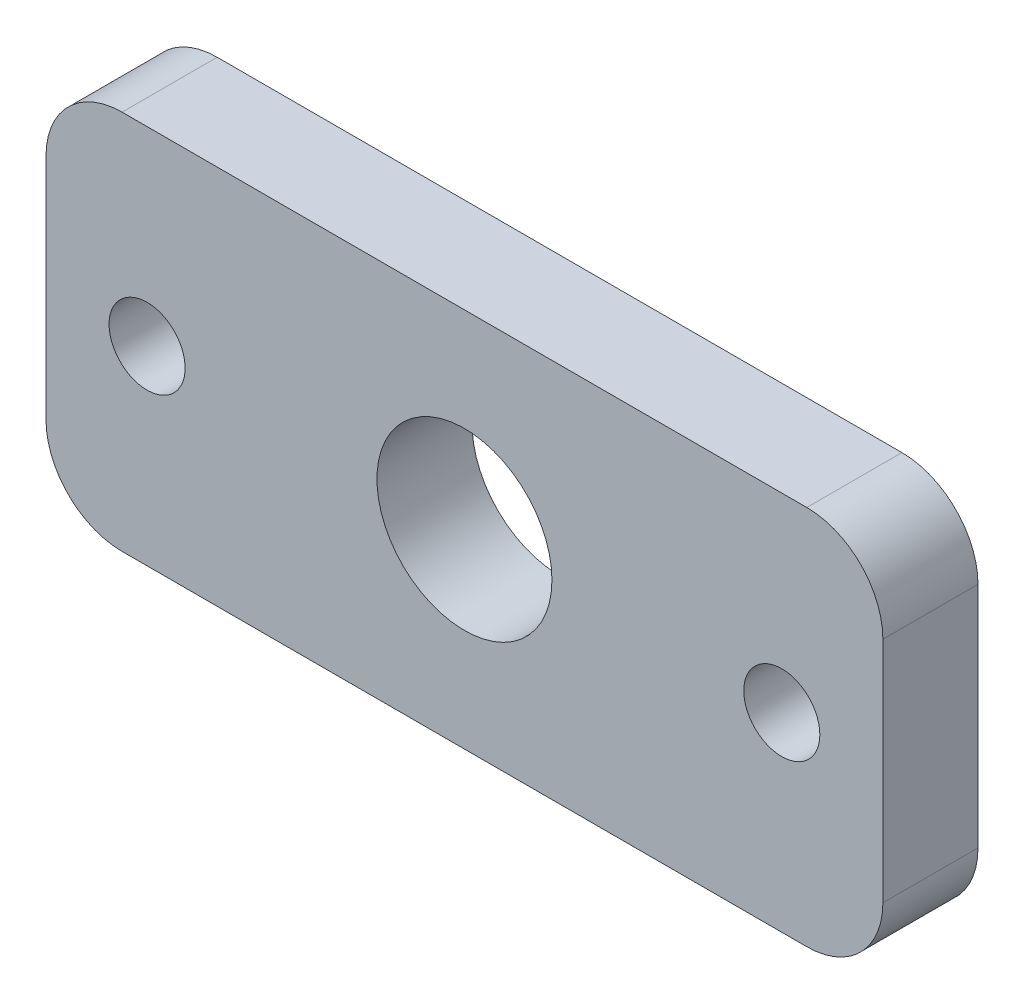
SolidWorks part; units mm, degrees
ref_plane "Front Plane" through (0, 0, 0) normal (0, 0, 1) x (1, 0, 0)
ref_plane "Top Plane" through (0, 0, 0) normal (0, 1, 0) x (1, 0, 0)
ref_plane "Right Plane" through (0, 0, 0) normal (1, 0, 0) x (0, 0, -1)
sketch "Sketch1" plane through (0, 0, 0) normal (0, 0, 1) x (1, 0, 0)
  line L1 (-27.94, 12.7) -> (27.94, 12.7)
  line L2 (-27.94, 12.7) -> (-27.94, -12.7)
  line L3 (-27.94, -12.7) -> (27.94, -12.7)
  line L4 (27.94, 12.7) -> (27.94, -12.7)
  line L5 (-27.94, 12.7) -> (27.94, -12.7) construction
  line L6 (-27.94, -12.7) -> (27.94, 12.7) construction
  circle A0 centre (0, 0) radius 5.842
  point P0 (0, 0)
  dimension "D3" = 11.684
  dimension "D1" = 25.4
  dimension "D2" = 55.88
extrude "Boss-Extrude1" add sketch "Sketch1" along normal mid plane 6.35
sketch "Sketch2" plane through (0, 0, 3.175) normal (0, 0, 1) x (1, 0, 0)
  line L1 (0, 0) -> (0, 6.9804) construction
  circle A0 centre (21.19, 0) radius 2.54
  circle A1 centre (-21.19, 0) radius 2.54
  dimension "D1" = 5.08
  dimension "D2" = 42.38
extrude "4-40" cut sketch "Sketch2" against normal through all
fillet "Fillet1" radius 5.08 4 edges at (-27.94, -12.7, 0) (27.94, -12.7, 0) (27.94, 12.7, 0) (-27.94, 12.7, 0)
